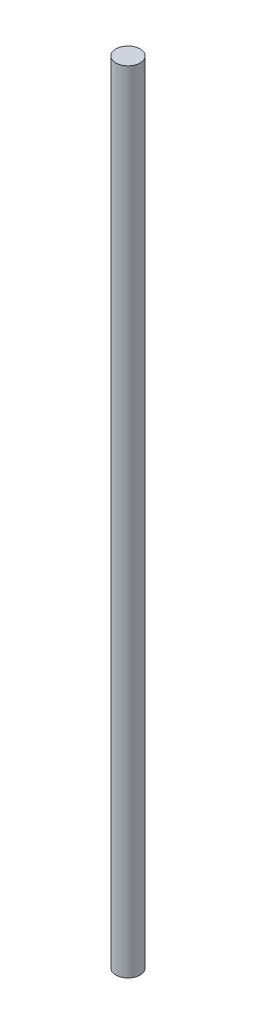
SolidWorks part; units mm, degrees
ref_plane "Plan de face" through (0, 0, 0) normal (0, 0, 1) x (1, 0, 0)
ref_plane "Plan de dessus" through (0, 0, 0) normal (0, 1, 0) x (1, 0, 0)
ref_plane "Plan de droite" through (0, 0, 0) normal (1, 0, 0) x (0, 0, -1)
sketch "Esquisse1" plane through (0, 0, 0) normal (0, 1, 0) x (1, 0, 0)
  circle A0 centre (0, 0) radius 20
  dimension "D1" = 40
extrude "Boss.-Extru.1" add sketch "Esquisse1" along normal blind 1300
